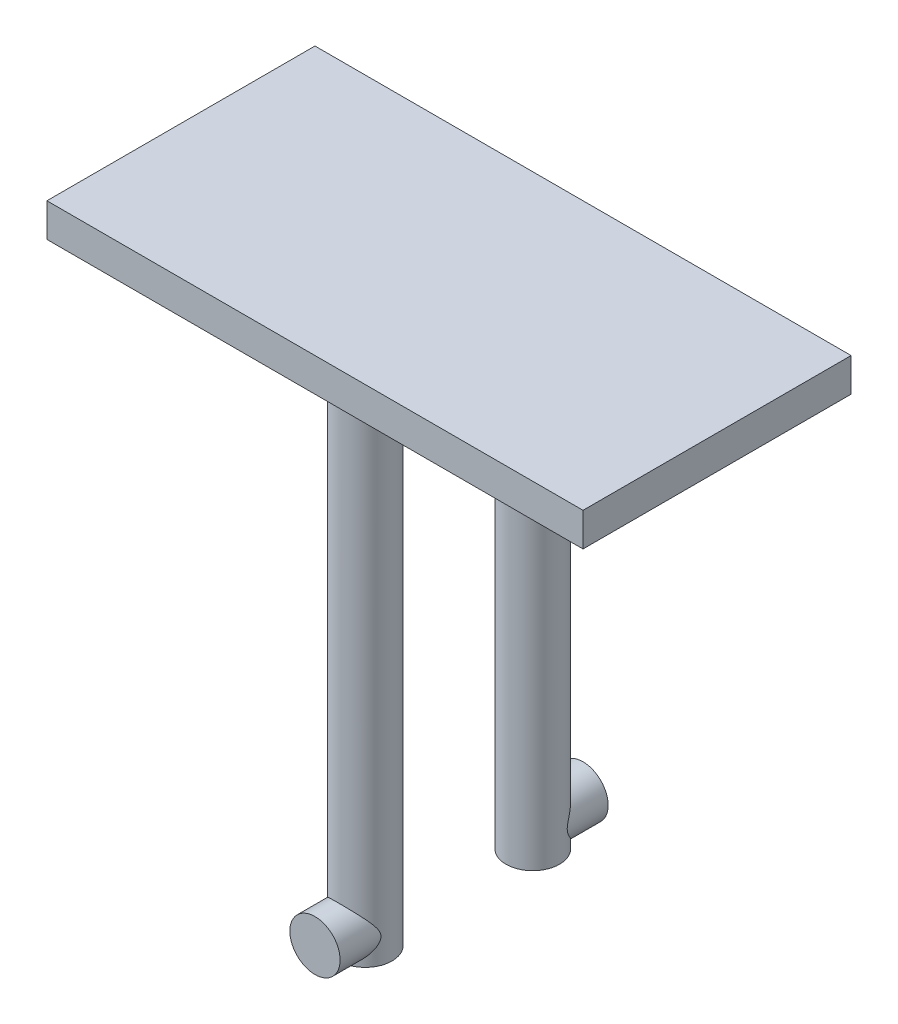
SolidWorks part; units mm, degrees
ref_plane "前视基准面" through (0, 0, 0) normal (0, 0, 1) x (1, 0, 0)
ref_plane "上视基准面" through (0, 0, 0) normal (0, 1, 0) x (1, 0, 0)
ref_plane "右视基准面" through (0, 0, 0) normal (1, 0, 0) x (0, 0, -1)
other "Configuration Table"
sketch "草图1" plane through (0, 0, 0) normal (0, 1, 0) x (1, 0, 0)
  line L1 (-80, 40) -> (80, 40)
  line L2 (-80, 40) -> (-80, -40)
  line L3 (-80, -40) -> (80, -40)
  line L4 (80, 40) -> (80, -40)
  line L5 (-80, 40) -> (80, -40) construction
  line L6 (-80, -40) -> (80, 40) construction
  point P0 (0, 0)
  dimension "D1" = 160
  dimension "D2" = 80
extrude "凸台-拉伸1" add sketch "草图1" along normal blind 10
sketch "草图2" plane through (0, 0, 0) normal (0, -1, 0) x (1, 0, 0)
  line L0 (0, 0) -> (50000, 0) construction
  line L1 (0, -0.4822) -> (0, -9.5912) construction
  circle A0 centre (0, 25) radius 8
  circle A1 centre (0, -25) radius 8
  dimension "D1" = 16
  dimension "D2" = 25
extrude "凸台-拉伸2" add sketch "草图2" along normal blind 150
sketch "草图3" plane through (0, 0, -40) normal (0, 0, -1) x (-1, 0, 0)
  line L0 (-8, -150) -> (8, -150) construction
  circle A0 centre (0, -142.5) radius 7.5
  dimension "D1" = 7.5
extrude "凸台-拉伸3" add sketch "草图3" against normal blind 15
sketch "草图4" plane through (0, 0, 40) normal (0, 0, 1) x (1, 0, 0)
  circle A0 centre (0, -142.5) radius 7.5
  dimension "D1" = 15
extrude "凸台-拉伸4" add sketch "草图4" against normal blind 15
